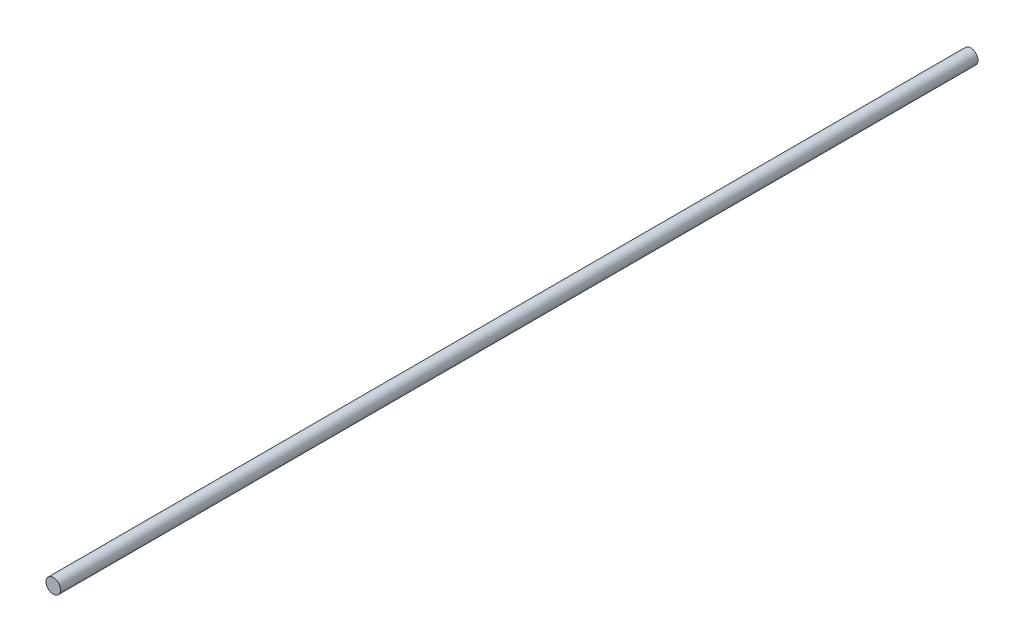
SolidWorks part; units mm, degrees
ref_plane "前视基准面" through (0, 0, 0) normal (0, 0, 1) x (1, 0, 0)
ref_plane "上视基准面" through (0, 0, 0) normal (0, 1, 0) x (1, 0, 0)
ref_plane "右视基准面" through (0, 0, 0) normal (1, 0, 0) x (0, 0, -1)
other "Configuration Table"
sketch "草图1" plane through (0, 0, 0) normal (0, 0, 1) x (1, 0, 0)
  circle A0 centre (0, 0) radius 3
  dimension "D1" = 6
extrude "凸台-拉伸1" add sketch "草图1" along normal blind 380
